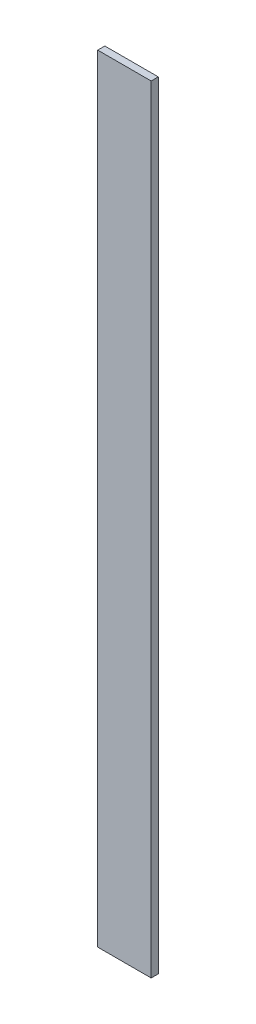
SolidWorks part; units mm, degrees
ref_plane "Front Plane" through (0, 0, 0) normal (0, 0, 1) x (1, 0, 0)
ref_plane "Top Plane" through (0, 0, 0) normal (0, 1, 0) x (1, 0, 0)
ref_plane "Right Plane" through (0, 0, 0) normal (1, 0, 0) x (0, 0, -1)
sketch "Sketch1" plane through (0, 0, 0) normal (0, 0, 1) x (1, 0, 0)
  line L1 (-7.5, -109) -> (7.5, -109)
  line L2 (-7.5, -109) -> (-7.5, 109)
  line L3 (-7.5, 109) -> (7.5, 109)
  line L4 (7.5, -109) -> (7.5, 109)
  line L5 (0, 109) -> (0, -109) construction
  line L6 (-7.5, 0) -> (7.5, 0) construction
  point P0 (0, 0)
  dimension "D1" = 218
  dimension "D2" = 15
extrude "Boss-Extrude1" add sketch "Sketch1" along normal blind 2
